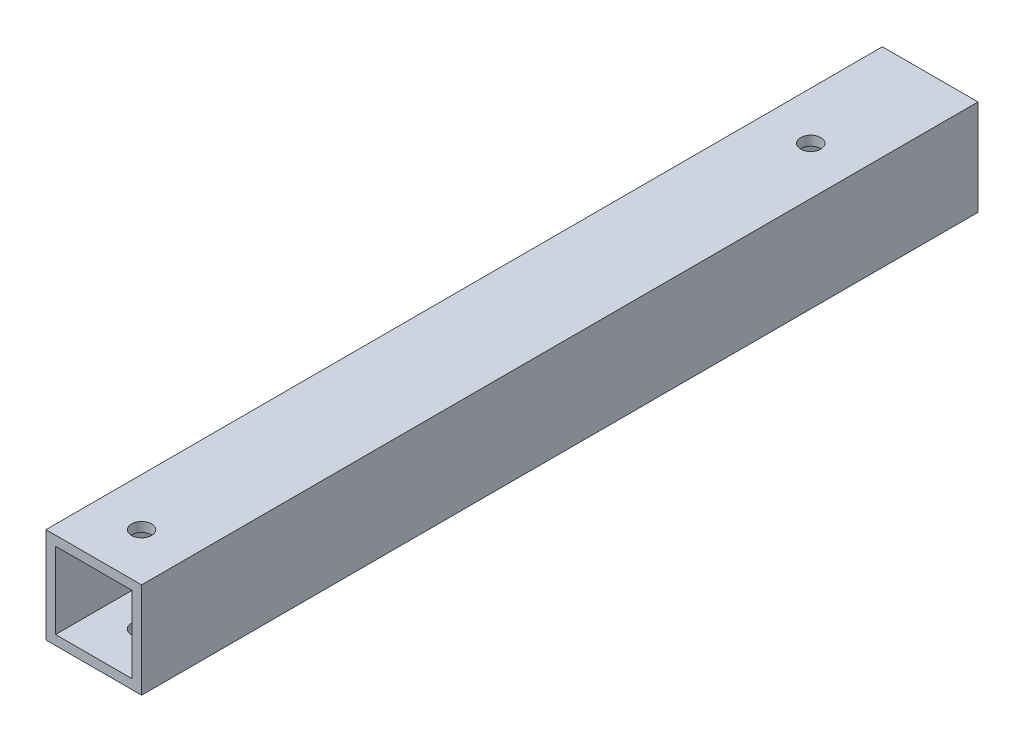
SolidWorks part; units mm, degrees
ref_plane "前视基准面" through (0, 0, 0) normal (0, 0, 1) x (1, 0, 0)
ref_plane "上视基准面" through (0, 0, 0) normal (0, 1, 0) x (1, 0, 0)
ref_plane "右视基准面" through (0, 0, 0) normal (1, 0, 0) x (0, 0, -1)
other "Configuration Table"
sketch "草图1" plane through (0, 0, 0) normal (0, 0, 1) x (1, 0, 0)
  line L1 (-10, -10) -> (10, -10)
  line L2 (-10, -10) -> (-10, 10)
  line L3 (-10, 10) -> (10, 10)
  line L4 (10, -10) -> (10, 10)
  line L5 (-10, -10) -> (10, 10) construction
  line L6 (-10, 10) -> (10, -10) construction
  line L7 (-8, -8) -> (8, -8)
  line L8 (-8, -8) -> (-8, 8)
  line L9 (-8, 8) -> (8, 8)
  line L10 (8, -8) -> (8, 8)
  line L11 (-8, -8) -> (8, 8) construction
  line L12 (-8, 8) -> (8, -8) construction
  point P0 (0, 0)
  point P6 (0, 0)
  dimension "D1" = 20
  dimension "D2" = 2
extrude "凸台-拉伸1" add sketch "草图1" along normal blind 175 contours L1 L4 L3 L2 L10 L7 L8 L9
sketch "草图2" plane through (0, 10, 0) normal (0, 1, 0) x (1, 0, 0)
  line L0 (0, -175) -> (0, 0) construction
  line L1 (-10, -175) -> (10, -175) construction
  line L2 (-10, 0) -> (10, 0) construction
  circle A0 centre (0, -165) radius 2.1
  circle A1 centre (0, -25) radius 2.1
  dimension "D1" = 4.2
  dimension "D2" = 4.2
  dimension "D3" = 10
  dimension "D4" = 25
extrude "切除-拉伸1" cut sketch "草图2" against normal through all
